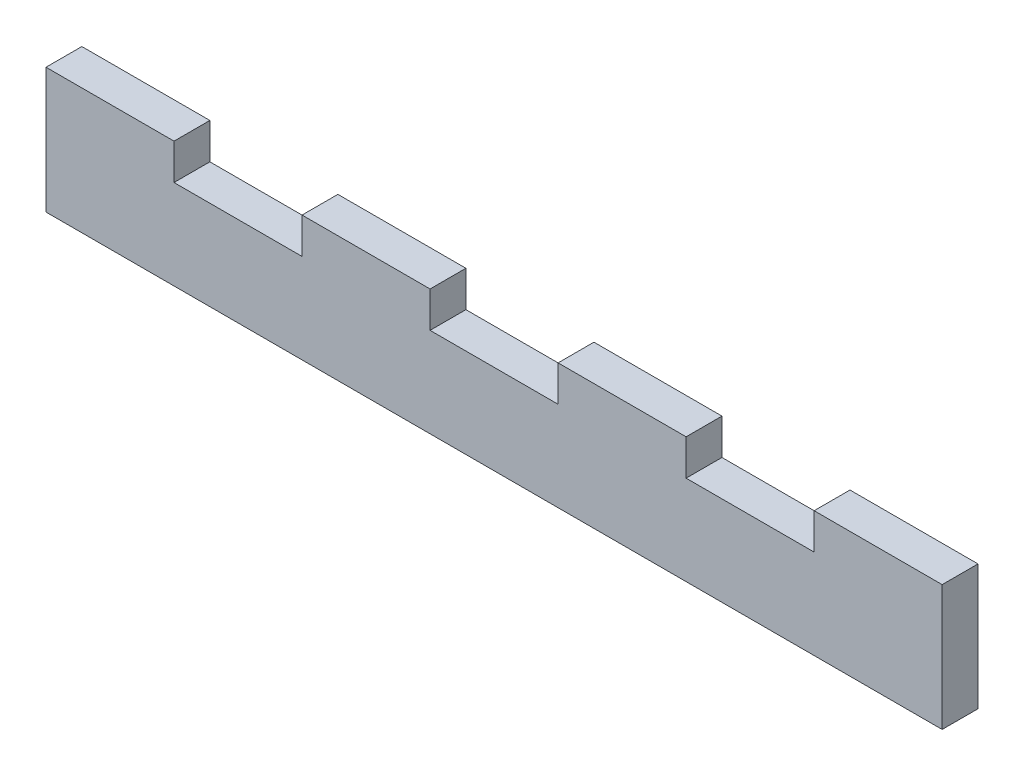
SolidWorks part; units mm, degrees
ref_plane "Front Plane" through (0, 0, 0) normal (0, 0, 1) x (1, 0, 0)
ref_plane "Top Plane" through (0, 0, 0) normal (0, 1, 0) x (1, 0, 0)
ref_plane "Right Plane" through (0, 0, 0) normal (1, 0, 0) x (0, 0, -1)
sketch "Sketch1" plane through (0, 0, 0) normal (0, 0, 1) x (1, 0, 0)
  line L1 (63.5, -8.89) -> (-63.5, -8.89)
  line L2 (63.5, -8.89) -> (63.5, 8.89)
  line L3 (63.5, 8.89) -> (-63.5, 8.89)
  line L4 (-63.5, -8.89) -> (-63.5, 8.89)
  line L5 (63.5, -8.89) -> (-63.5, 8.89) construction
  line L6 (63.5, 8.89) -> (-63.5, -8.89) construction
  point P0 (0, 0)
  dimension "D1" = 127
  dimension "D2" = 17.78
extrude "Boss-Extrude1" add sketch "Sketch1" along normal blind 5.08
sketch "Sketch2" plane through (0, 8.89, 0) normal (0, 1, 0) x (1, 0, 0)
  line L6 (63.5, -5.08) -> (-63.5, -5.08) construction
  line L15 (45.3571, -5.08) -> (27.2143, -5.08)
  line L16 (45.3571, -5.08) -> (45.3571, 0)
  line L18 (45.3571, 0) -> (27.2143, 0)
  line L19 (27.2143, -5.08) -> (27.2143, 0)
  line L20 (63.5, 0) -> (-63.5, 0) construction
  line L22 (63.5, 0) -> (45.3571, 0) construction
  line L23 (9.0714, -5.08) -> (-9.0714, -5.08)
  line L24 (9.0714, -5.08) -> (9.0714, 0)
  line L25 (9.0714, 0) -> (-9.0714, 0)
  line L26 (-9.0714, -5.08) -> (-9.0714, 0)
  line L27 (-27.2143, -5.08) -> (-45.3571, -5.08)
  line L28 (-27.2143, -5.08) -> (-27.2143, 0)
  line L29 (-27.2143, 0) -> (-45.3571, 0)
  line L30 (-45.3571, -5.08) -> (-45.3571, 0)
  line L31 (27.2143, 0) -> (9.0714, 0) construction
  line L32 (-9.0714, 0) -> (-27.2143, 0) construction
  line L33 (-45.3571, 0) -> (-63.5, 0) construction
extrude "Cut-Extrude1" cut sketch "Sketch2" against normal blind 5.08
equation "\"foamcore\"= .1in"
equation "\"MDF\"= .2in"
equation "\"GMaterial\"= \"MDF\""
equation "\"D1@Cut-Extrude1\"=\"GMaterial\""
equation "\"D1@Boss-Extrude1\"=\"GMaterial\""
